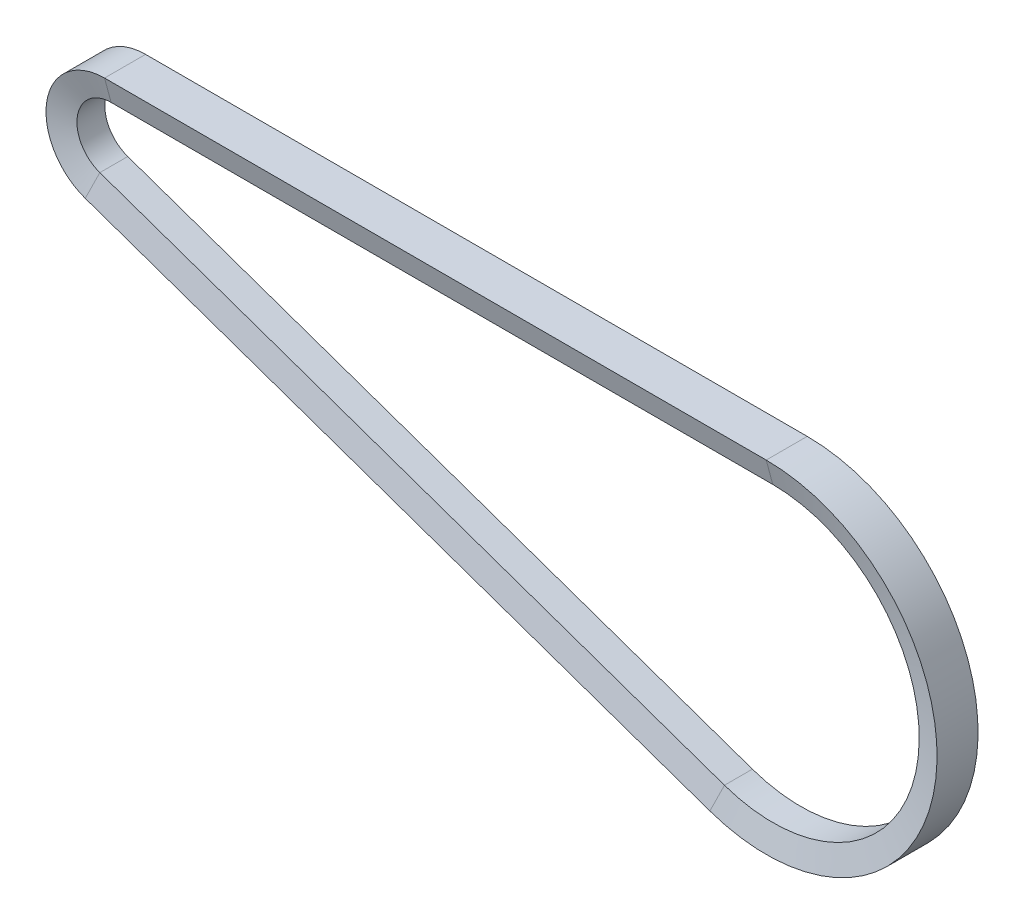
SolidWorks part; units mm, degrees
material "NBR"
ref_plane "Plano frontal" through (0, 0, 0) normal (0, 0, 1) x (1, 0, 0)
ref_plane "Plano superior" through (0, 0, 0) normal (0, 1, 0) x (1, 0, 0)
ref_plane "Plano direito" through (0, 0, 0) normal (1, 0, 0) x (0, 0, -1)
sketch "Esboço1" plane through (0, 0, 0) normal (0, 0, 1) x (1, 0, 0)
  line L0 (0, 0) -> (-133.0627, 0)
  line L1 (-137.6804, -27.2166) -> (118.2728, -116.6424)
  line L2 (138.0627, 0) -> (5, 0)
  arc A0 (-133.0627, 0) -> (-137.6804, -27.2166) centre (-133.0627, -14) ccw
  arc A1 (118.2728, -116.6424) -> (138.0627, 0) centre (138.0627, -60) ccw
  dimension "D1" = 14
  dimension "D2" = 60
  dimension "D3" = 275
  dimension "D4" = 5
sketch "Esboço2" plane through (0, 0, 0) normal (1, 0, 0) x (0, 0, -1)
  line L0 (-8.4, 10) -> (8.4, 10)
  line L1 (8.4, 10) -> (5.7205, 0)
  line L2 (5.7205, 0) -> (-5.7205, 0)
  line L3 (-5.7205, 0) -> (-8.4, 10)
  point P2 (0, 0)
  dimension "D1" = 30
  dimension "D2" = 16.8
  dimension "D3" = 10
sweep "Varredura1" add profiles "Esboço2" path "Esboço1"
sketch "Esboço3" plane through (0, 0, 0) normal (1, 0, 0) x (0, 0, -1)
  line L4 (-8.4, 10) -> (-5.7205, 0)
  line L5 (-5.7205, 0) -> (5.7205, 0)
  line L6 (5.7205, 0) -> (8.4, 10)
  line L7 (8.4, 10) -> (-8.4, 10)
  line L8 (-8.4, 10) -> (-5.7205, 0)
  line L9 (-5.7205, 0) -> (5.7205, 0)
  line L10 (5.7205, 0) -> (8.4, 10)
  line L11 (8.4, 10) -> (-8.4, 10)
  dimension "D1" = 0
extrude "Ressalto-extrusão1" add sketch "Esboço3" along normal up to surface (5 mm away) up to face at (5, 5, 0)
